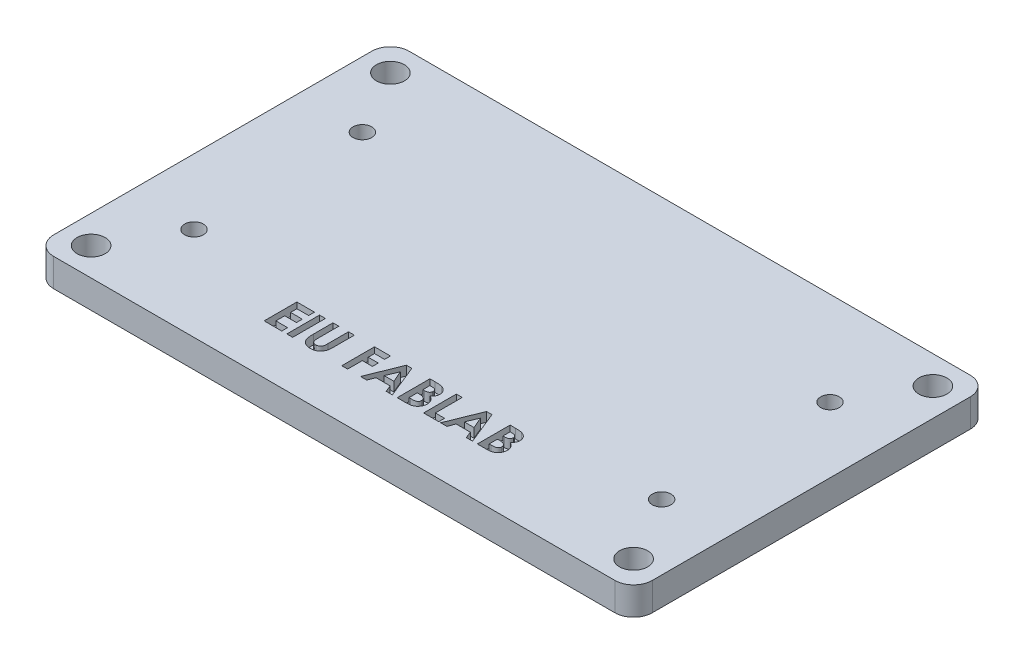
SolidWorks part; units mm, degrees
ref_plane "Front Plane" through (0, 0, 0) normal (0, 0, 1) x (1, 0, 0)
ref_plane "Top Plane" through (0, 0, 0) normal (0, 1, 0) x (1, 0, 0)
ref_plane "Right Plane" through (0, 0, 0) normal (1, 0, 0) x (0, 0, -1)
sketch "Sketch1" plane through (0, 0, 0) normal (0, 1, 0) x (1, 0, 0)
  line L0 (-29, 16) -> (29, 16)
  line L1 (-30, -19) -> (30, -19)
  line L2 (-32, -17) -> (-32, 17)
  line L3 (-30, 19) -> (30, 19)
  line L4 (32, -17) -> (32, 17)
  line L5 (-32, -19) -> (32, 19) construction
  line L6 (-32, 19) -> (32, -19) construction
  line L7 (29, -16) -> (29, 16)
  line L8 (-29, -16) -> (29, -16)
  line L9 (-29, -16) -> (-29, 16)
  line L10 (32, -19) -> (32, 19) construction
  line L11 (-32, 19) -> (32, 19) construction
  line L12 (-32, -19) -> (32, -19) construction
  line L13 (-32, -19) -> (-32, 19) construction
  line L14 (-29, 0) -> (29, 0) construction
  line L15 (0, 16) -> (0, -16) construction
  line L16 (-25, -9) -> (-25, 9)
  line L17 (25, -9) -> (25, 9)
  circle A0 centre (-29, 16) radius 1.5
  circle A1 centre (29, 16) radius 1.5
  circle A2 centre (-29, -16) radius 1.5
  circle A3 centre (29, -16) radius 1.5
  arc A4 (32, 17) -> (30, 19) centre (30, 17) ccw
  arc A5 (32, -17) -> (30, -19) centre (30, -17) cw
  arc A6 (-32, -17) -> (-30, -19) centre (-30, -17) ccw
  arc A7 (-32, 17) -> (-30, 19) centre (-30, 17) cw
  circle A8 centre (-25, 9) radius 1
  circle A9 centre (-25, -9) radius 1
  circle A10 centre (25, -9) radius 1
  circle A11 centre (25, 9) radius 1
  point P0 (0, 0)
  point P33 (-25, 0)
  point P39 (25, 0)
  dimension "D4" = 3
  dimension "D5" = 3
  dimension "D6" = 3
  dimension "D7" = 3
  dimension "D8" = 2
  dimension "D9" = 2
  dimension "D10" = 2
  dimension "D1" = 64
  dimension "D2" = 38
  dimension "D11" = 18
  dimension "D12" = 7
  dimension "D3" = 3
extrude "Boss-Extrude1" add sketch "Sketch1" along normal blind 3
sketch "Sketch2" plane through (0, 3, 0) normal (0, 1, 0) x (1, 0, 0)
  text T0 "<b>EIU FABLAB</b>"
extrude "Cut-Extrude3" cut sketch "Sketch2" against normal blind 1
